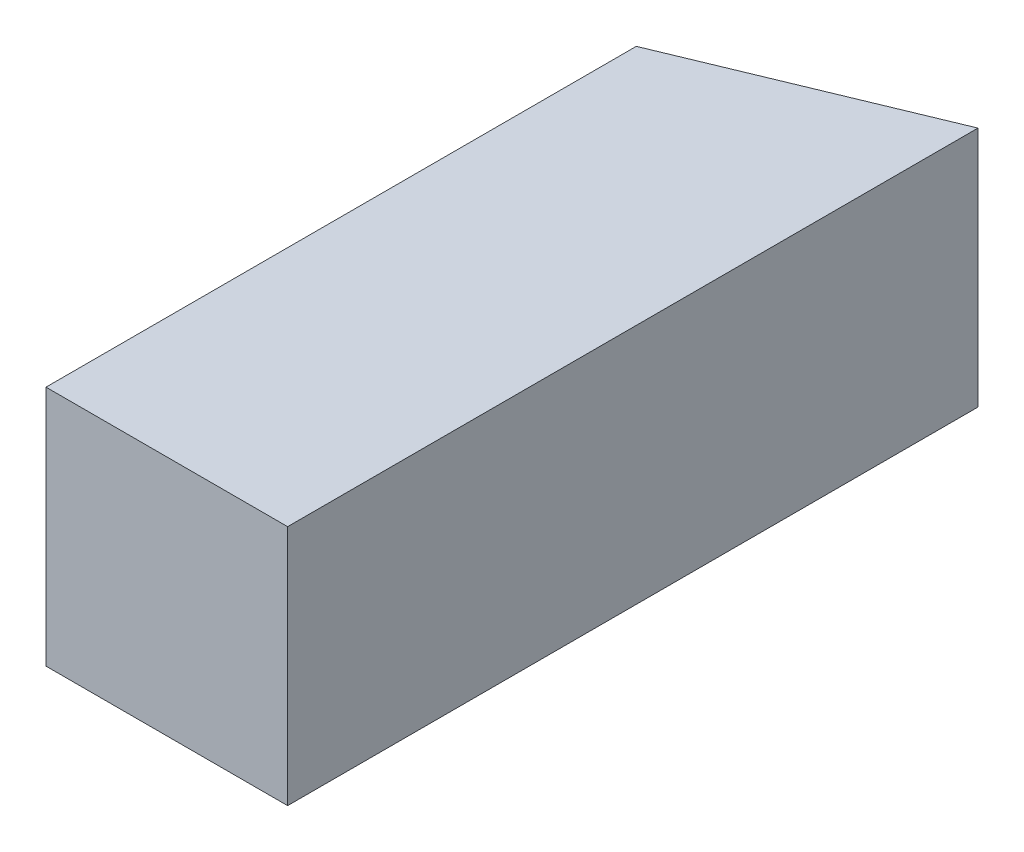
SolidWorks part; units mm, degrees
ref_plane "Front Plane" through (0, 0, 0) normal (0, 0, 1) x (1, 0, 0)
ref_plane "Top Plane" through (0, 0, 0) normal (0, 1, 0) x (1, 0, 0)
ref_plane "Right Plane" through (0, 0, 0) normal (1, 0, 0) x (0, 0, -1)
sketch "Sketch1" plane through (0, 0, 0) normal (0, 0, 1) x (1, 0, 0)
  line L1 (-44.45, -44.45) -> (44.45, -44.45)
  line L2 (-44.45, -44.45) -> (-44.45, 44.45)
  line L3 (-44.45, 44.45) -> (44.45, 44.45)
  line L4 (44.45, -44.45) -> (44.45, 44.45)
  line L5 (-44.45, -44.45) -> (44.45, 44.45) construction
  line L6 (-44.45, 44.45) -> (44.45, -44.45) construction
  point P0 (0, 0)
  dimension "D1" = 88.9
  dimension "D2" = 88.9
extrude "Boss-Extrude1" add sketch "Sketch1" along normal blind 254
sketch "Sketch2" plane through (0, -44.45, 0) normal (0, -1, 0) x (1, 0, 0)
  line L0 (44.45, 0) -> (-44.45, 36.8236)
  line L4 (-44.45, 0) -> (44.45, 0)
  line L5 (44.45, 0) -> (44.45, 254)
  line L6 (44.45, 254) -> (-44.45, 254)
  line L7 (-44.45, 254) -> (-44.45, 0)
  line L8 (-44.45, 0) -> (44.45, 0)
  line L11 (-44.45, 36.8236) -> (-44.45, 0)
  dimension "D2" = 22.5
  dimension "D1" = 0
extrude "Cut-Extrude1" cut sketch "Sketch2" against normal up to next
